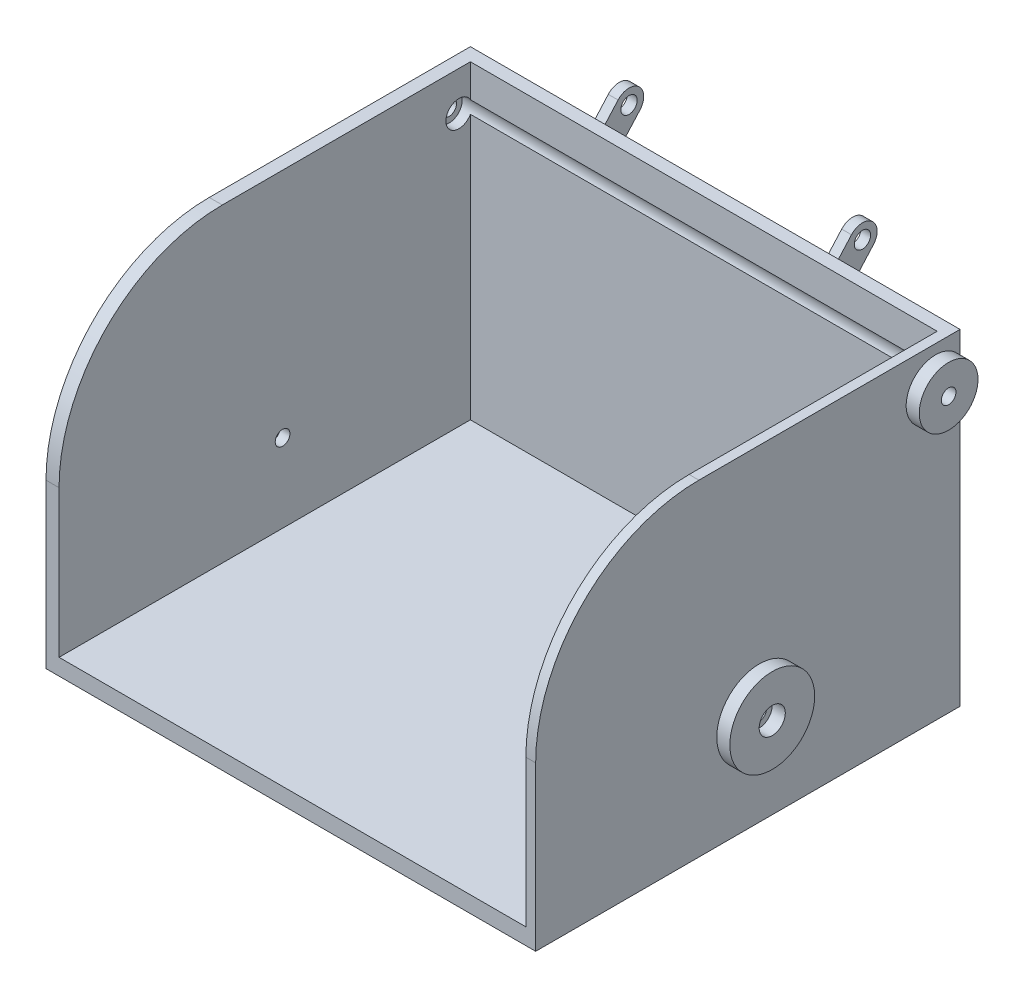
SolidWorks part; units mm, degrees
material "PLA"
ref_plane "Front Plane" through (0, 0, 0) normal (0, 0, 1) x (1, 0, 0)
ref_plane "Top Plane" through (0, 0, 0) normal (0, 1, 0) x (1, 0, 0)
ref_plane "Right Plane" through (0, 0, 0) normal (1, 0, 0) x (0, 0, -1)
sketch "Sketch1" plane through (0, 0, 0) normal (1, 0, 0) x (0, 0, -1)
  line L0 (0, 0) -> (-130, 0)
  line L1 (-130, 0) -> (-130, 50)
  line L2 (-80, 100) -> (0, 100)
  line L3 (0, 100) -> (0, 0)
  arc A0 (-130, 50) -> (-80, 100) centre (-80, 50) cw
  dimension "D1" = 130
  dimension "D2" = 100
  dimension "D3" = 50
extrude "Boss-Extrude1" add sketch "Sketch1" along normal blind 150 contours A0 L2 L3 L0 L1
sketch "Sketch2" plane through (0, 100, 0) normal (0, 1, 0) x (1, 0, 0)
  line L0 (150, 0) -> (0, 0) construction
  line L1 (4, -4) -> (147, -4)
  line L2 (4, -4) -> (4, -135)
  line L3 (4, -135) -> (147, -135)
  line L4 (147, -4) -> (147, -135)
  line L5 (150, -80) -> (150, 0) construction
  line L6 (0, -80) -> (0, 0) construction
  line L8 (150, -130) -> (0, -130) construction
  dimension "D1" = 4
  dimension "D2" = 3
  dimension "D3" = 4
  dimension "D4" = 5
extrude "Cut-Extrude1" cut sketch "Sketch2" against normal offset from surface (95 mm away) 5 up to face at (75, 0, 65)
ref_plane "Plane1" through (75.5, 0, 0) normal (1, 0, 0) x (0, 0, -1)
ref_plane "Plane2" through (111.25, 0, 0) normal (1, 0, 0) x (0, 0, -1)
ref_plane "Plane3" through (39.75, 0, 0) normal (1, 0, 0) x (0, 0, -1)
sketch "Sketch3" plane through (111.25, 0, 0) normal (1, 0, 0) x (0, 0, -1)
  line L0 (0, 100) -> (0, 86.4837)
  line L1 (0, 86.4837) -> (10.7098, 98.4837)
  line L2 (3.9952, 104.4764) -> (0, 100)
  arc A0 (10.7098, 98.4837) -> (3.9952, 104.4764) centre (7.3525, 101.4801) ccw
  circle A1 centre (7.3525, 101.4801) radius 2.5
  dimension "D1" = 2
  dimension "D2" = 5
  dimension "D3" = 6
  dimension "D4" = 12
extrude "Boss-Extrude2" add sketch "Sketch3" along normal mid plane 3
mirror "Mirror1" about plane through (75.5, 0, 0) normal (1, 0, 0) of "Boss-Extrude2"
sketch "Sketch4" plane through (150, 0, 0) normal (1, 0, 0) x (0, 0, -1)
  line L0 (-7.5037, 88) -> (-61.5315, 29) construction
  line L1 (0, 0) -> (-130, 0) construction
  line L2 (-80, 100) -> (0, 100) construction
  circle A0 centre (-61.5315, 29) radius 2.25
  circle A1 centre (-7.5037, 88) radius 4
  dimension "D4" = 8
  dimension "D5" = 4.5
  dimension "D1" = 80
  dimension "D2" = 29
  dimension "D3" = 12
extrude "Cut-Extrude2" cut sketch "Sketch4" against normal up to next
mirror "Mirror2" about plane through (75.5, 0, 0) normal (1, 0, 0) of "Cut-Extrude2"
sketch "Sketch5" plane through (150, 0, 0) normal (1, 0, 0) x (0, 0, -1)
  circle A0 centre (-7.5, 88) radius 9
  circle A1 centre (-7.5, 88) radius 2.25
  circle A2 centre (-61.53, 29) radius 13
  circle A3 centre (-61.53, 29) radius 4
extrude "Boss-Extrude3" add sketch "Sketch5" along normal blind 4
mirror "Mirror3" about plane through (75.5, 0, 0) normal (1, 0, 0) of "Boss-Extrude3"
equation "\"forward_length\"= 130"
equation "\"height\"= 100"
equation "\"eslabon_AB\"=80"
